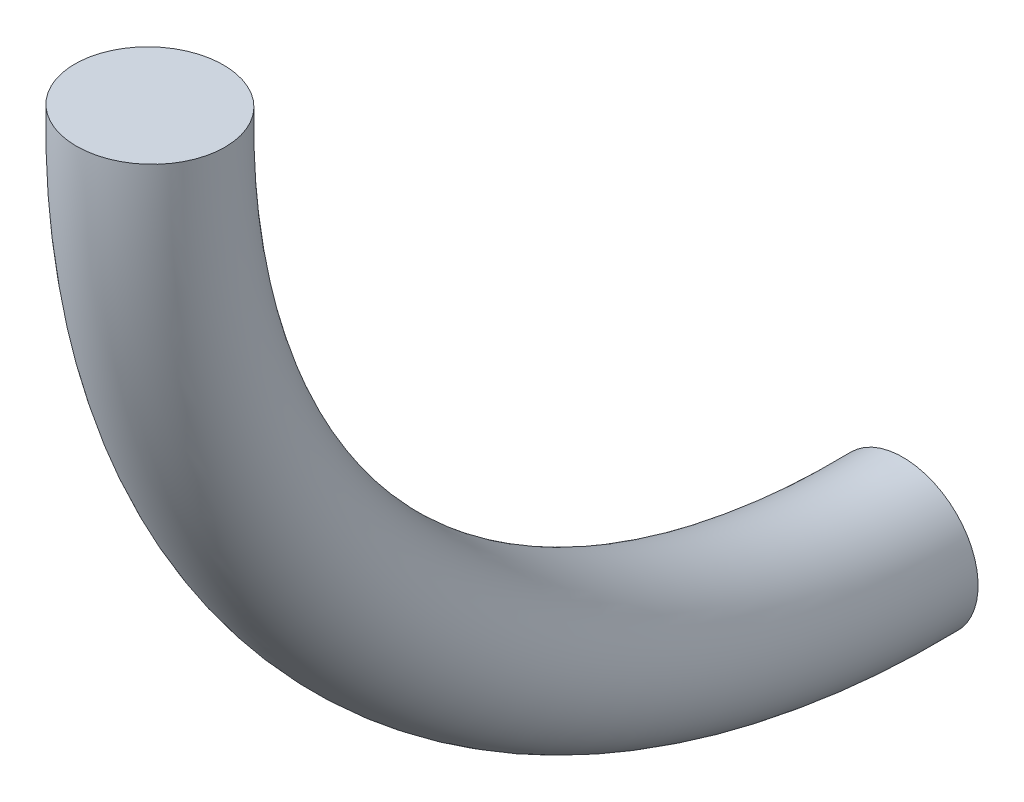
SolidWorks part; units mm, degrees
ref_plane "Front Plane" through (0, 0, 0) normal (0, 0, 1) x (1, 0, 0)
ref_plane "Top Plane" through (0, 0, 0) normal (0, 1, 0) x (1, 0, 0)
ref_plane "Right Plane" through (0, 0, 0) normal (1, 0, 0) x (0, 0, -1)
ref_plane "Plane1" through (38, 0, 0) normal (1, 0, 0) x (0, 0, -1)
ref_plane "Plane2" through (-38, 0, 0) normal (1, 0, 0) x (0, 0, -1)
ref_plane "Plane4" through (0, 0, 348) normal (0, 0, 1) x (1, 0, 0)
sketch "Sketch3" plane through (0, 0, 0) normal (1, 0, 0) x (0, 0, -1)
  line L0 (0, 0) -> (400, 0) construction
  line L1 (400, 0) -> (400, -400) construction
  arc A0 (0, 0) -> (400, -400) centre (391.55, -8.45) ccw
  dimension "D1" = 400
  dimension "D2" = 400
sweep "Sweep1" add path "Sketch3" circular profile diameter 78 parameters "D3"=78
